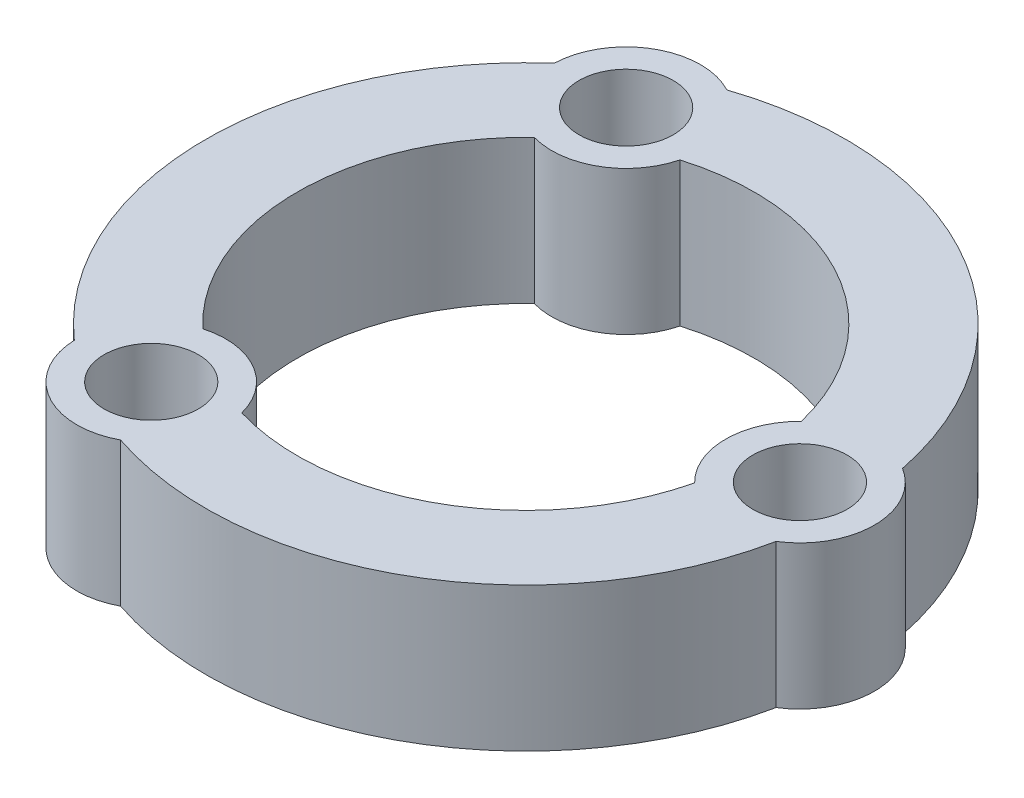
SolidWorks part; units mm, degrees
material "ABS"
ref_plane "Front Plane" through (0, 0, 0) normal (0, 0, 1) x (1, 0, 0)
ref_plane "Top Plane" through (0, 0, 0) normal (0, 1, 0) x (1, 0, 0)
ref_plane "Right Plane" through (0, 0, 0) normal (1, 0, 0) x (0, 0, -1)
sketch "Sketch1" plane through (0, 0, 0) normal (0, 1, 0) x (1, 0, 0)
  arc A0 (21.7892, 4.3921) -> (-7.0909, 21.0661) centre (0, 0) ccw
  arc A1 (15.4392, 3.7047) -> (15.4392, -3.7047) centre (19.0525, 0) ccw
  circle A2 centre (-9.5263, -16.4999) radius 3.175 construction
  circle A3 centre (-9.5262, 16.4999) radius 3.175 construction
  circle A4 centre (19.0525, 0) radius 3.175 construction
  circle A5 centre (-9.5262, 16.4999) radius 3.175
  circle A6 centre (19.0525, 0) radius 3.175
  circle A7 centre (-9.5263, -16.4999) radius 3.175
  arc A8 (-4.5112, -15.2231) -> (-10.928, -11.5184) centre (-9.5263, -16.4999) ccw
  arc A9 (21.7892, -4.3921) -> (21.7892, 4.3921) centre (19.0525, 0) ccw
  arc A10 (-7.0909, 21.0661) -> (-14.6983, 16.674) centre (-9.5262, 16.4999) ccw
  arc A11 (15.4392, 3.7047) -> (-4.5112, 15.2231) centre (0, 0) ccw
  circle A12 centre (19.0525, 0) radius 5.175 construction
  arc A13 (-10.928, 11.5184) -> (-4.5112, 15.2231) centre (-9.5262, 16.4999) ccw
  circle A14 centre (-9.5262, 16.4999) radius 5.175 construction
  arc A15 (-10.928, 11.5184) -> (-10.928, -11.5184) centre (0, 0) ccw
  arc A16 (-14.6983, 16.674) -> (-14.6983, -16.674) centre (0, 0) ccw
  arc A17 (-4.5112, -15.2231) -> (15.4392, -3.7047) centre (0, 0) ccw
  arc A18 (-7.0909, -21.0661) -> (21.7892, -4.3921) centre (0, 0) ccw
  circle A19 centre (-9.5263, -16.4999) radius 5.175 construction
  arc A20 (-14.6983, -16.674) -> (-7.0909, -21.0661) centre (-9.5263, -16.4999) ccw
  point P1 (30.1365, 0)
  point P20 (-4.9245, 20.2425)
  point P29 (-4.9245, -20.2425)
  dimension "D1" = 2
extrude "Boss-Extrude1" add sketch "Sketch1" along normal blind 10 contours A7 | A5 | A6 | A16 A20 A18 A9 A0 A10 A5 A6 A7 A17 A8 A15 A13 A11 A1
sketch "Sketch3" plane through (0, 10, 0) normal (0, 1, 0) x (1, 0, 0)
  circle A1 centre (19.0525, 0) radius 3.275
  arc A3 (15.4392, 3.7047) -> (15.4392, -3.7047) centre (19.0525, 0) ccw construction
  dimension "D1" = 6.55
extrude "Cut-Extrude1" cut sketch "Sketch3" against normal blind 7.5
pattern_circular "CirPattern1" count 3 every 120 about axis through (0, 0, 0) along (0, 1, 0) of "Cut-Extrude1"
